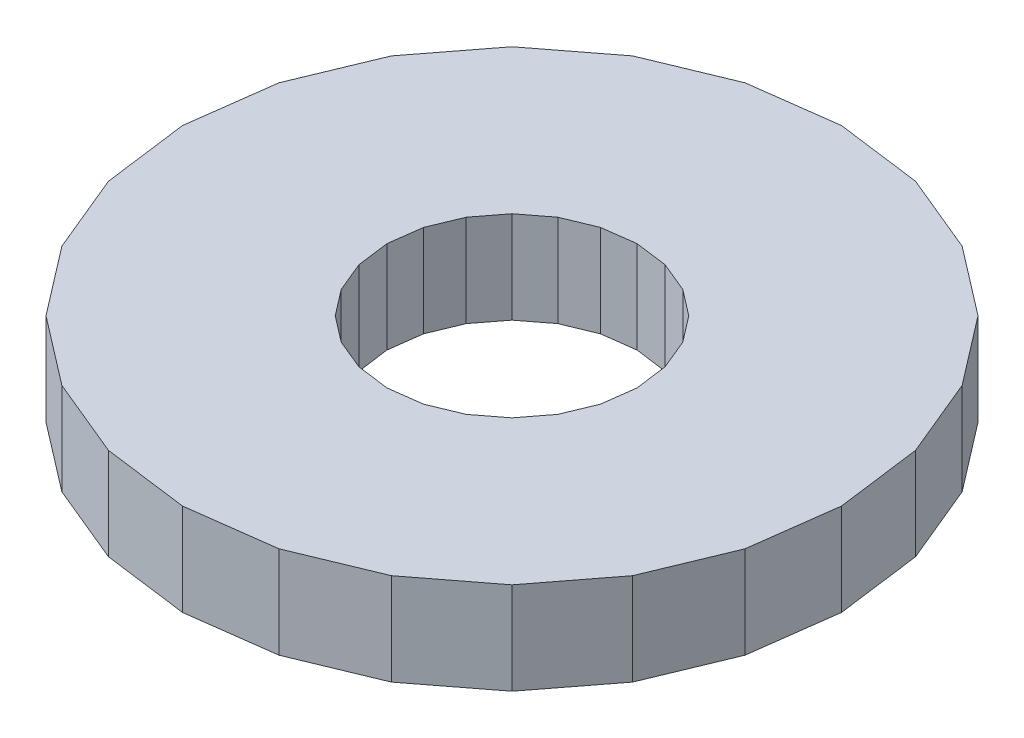
SolidWorks part; units mm, degrees
ref_plane "Front Plane" through (0, 0, 0) normal (0, 0, 1) x (1, 0, 0)
ref_plane "Top Plane" through (0, 0, 0) normal (0, 1, 0) x (1, 0, 0)
ref_plane "Right Plane" through (0, 0, 0) normal (1, 0, 0) x (0, 0, -1)
sketch "Sketch3" plane through (0, 0, 0) normal (0, 1, 0) x (1, 0, 0)
  line L0 (0, 0) -> (-25.8373, 0) construction
  line L1 (-68.1089, 0) -> (-65.7882, -17.6279)
  line L2 (-65.7882, -17.6279) -> (-58.9841, -34.0545)
  line L3 (-58.9841, -34.0545) -> (-48.1603, -48.1603)
  line L4 (-48.1603, -48.1603) -> (-34.0545, -58.9841)
  line L5 (-34.0545, -58.9841) -> (-17.6279, -65.7882)
  line L6 (-17.6279, -65.7882) -> (0, -68.1089)
  line L7 (0, -68.1089) -> (17.6279, -65.7882)
  line L8 (17.6279, -65.7882) -> (34.0545, -58.9841)
  line L9 (34.0545, -58.9841) -> (48.1603, -48.1603)
  line L10 (48.1603, -48.1603) -> (58.9841, -34.0545)
  line L11 (58.9841, -34.0545) -> (65.7882, -17.6279)
  line L12 (65.7882, -17.6279) -> (68.1089, 0)
  line L13 (68.1089, 0) -> (65.7882, 17.6279)
  line L14 (65.7882, 17.6279) -> (58.9841, 34.0545)
  line L15 (58.9841, 34.0545) -> (48.1603, 48.1603)
  line L16 (48.1603, 48.1603) -> (34.0545, 58.9841)
  line L17 (34.0545, 58.9841) -> (17.6279, 65.7882)
  line L18 (17.6279, 65.7882) -> (0, 68.1089)
  line L19 (0, 68.1089) -> (-17.6279, 65.7882)
  line L20 (-17.6279, 65.7882) -> (-34.0545, 58.9841)
  line L21 (-34.0545, 58.9841) -> (-48.1603, 48.1603)
  line L22 (-48.1603, 48.1603) -> (-58.9841, 34.0545)
  line L23 (-58.9841, 34.0545) -> (-65.7882, 17.6279)
  line L24 (-65.7882, 17.6279) -> (-68.1089, 0)
  line L25 (-25.8373, 0) -> (-24.9569, -6.6872)
  line L26 (-24.9569, -6.6872) -> (-22.3758, -12.9186)
  line L27 (-22.3758, -12.9186) -> (-18.2697, -18.2697)
  line L28 (-18.2697, -18.2697) -> (-12.9186, -22.3758)
  line L29 (-12.9186, -22.3758) -> (-6.6872, -24.9569)
  line L30 (-6.6872, -24.9569) -> (0, -25.8373)
  line L31 (0, -25.8373) -> (6.6872, -24.9569)
  line L32 (6.6872, -24.9569) -> (12.9186, -22.3758)
  line L33 (12.9186, -22.3758) -> (18.2697, -18.2697)
  line L34 (18.2697, -18.2697) -> (22.3758, -12.9186)
  line L35 (22.3758, -12.9186) -> (24.9569, -6.6872)
  line L36 (24.9569, -6.6872) -> (25.8373, 0)
  line L37 (25.8373, 0) -> (24.9569, 6.6872)
  line L38 (24.9569, 6.6872) -> (22.3758, 12.9186)
  line L39 (22.3758, 12.9186) -> (18.2697, 18.2697)
  line L40 (18.2697, 18.2697) -> (12.9186, 22.3758)
  line L41 (12.9186, 22.3758) -> (6.6872, 24.9569)
  line L42 (6.6872, 24.9569) -> (0, 25.8373)
  line L43 (0, 25.8373) -> (-6.6872, 24.9569)
  line L44 (-6.6872, 24.9569) -> (-12.9186, 22.3758)
  line L45 (-12.9186, 22.3758) -> (-18.2697, 18.2697)
  line L46 (-18.2697, 18.2697) -> (-22.3758, 12.9186)
  line L47 (-22.3758, 12.9186) -> (-24.9569, 6.6872)
  line L48 (-24.9569, 6.6872) -> (-25.8373, 0)
  line L49 (-68.1089, 0) -> (-25.8373, 0) construction
  circle A0 centre (0, 0) radius 67.5263 construction
  circle A1 centre (0, 0) radius 25.6163 construction
  dimension "D1" = 17.78
  dimension "D2" = 41.91
extrude "Boss-Extrude3" add sketch "Sketch3" along normal blind 19.05
